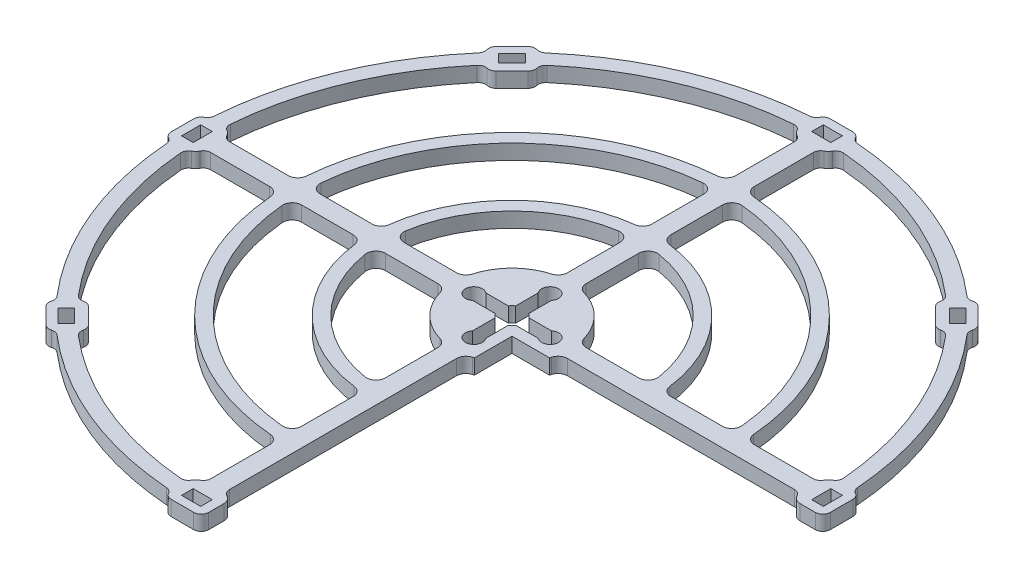
SolidWorks part; units mm, degrees
ref_plane "Front Plane" through (0, 0, 0) normal (0, 0, 1) x (1, 0, 0)
ref_plane "Top Plane" through (0, 0, 0) normal (0, 1, 0) x (1, 0, 0)
ref_plane "Right Plane" through (0, 0, 0) normal (1, 0, 0) x (0, 0, -1)
sketch "Sketch1" plane through (0, 0, 0) normal (0, 1, 0) x (1, 0, 0)
  line L0 (15.5, 0) -> (37.6667, 0) construction
  line L1 (2.5, -56.2778) -> (2.5, -59.7811)
  line L2 (37.6667, 0) -> (59.8333, 0) construction
  line L3 (2.5, -34.0751) -> (2.5, -37.5836)
  line L4 (-2.5, 85.9637) -> (2.5, 85.9637) construction
  line L5 (-2.5, 85.9637) -> (-2.5, -85.9637) construction
  line L6 (-2.5, -85.9637) -> (2.5, -85.9637) construction
  line L7 (2.5, 85.9637) -> (2.5, -85.9637) construction
  line L8 (-2.5, 85.9637) -> (2.5, -85.9637) construction
  line L9 (-2.5, -85.9637) -> (2.5, 85.9637) construction
  line L10 (-85.9637, 2.5) -> (85.9637, 2.5) construction
  line L11 (-85.9637, 2.5) -> (-85.9637, -2.5) construction
  line L12 (-85.9637, -2.5) -> (85.9637, -2.5) construction
  line L13 (85.9637, 2.5) -> (85.9637, -2.5) construction
  line L14 (-85.9637, 2.5) -> (85.9637, -2.5) construction
  line L15 (-85.9637, -2.5) -> (85.9637, 2.5) construction
  line L17 (2.5, -81.9619) -> (2.5, -85.9637)
  line L18 (34.0751, -2.5) -> (37.5836, -2.5)
  line L20 (81.9619, -2.5) -> (85.9637, -2.5)
  line L21 (56.2778, -2.5) -> (59.7811, -2.5)
  line L22 (59.8333, 0) -> (82, 0) construction
  arc A0 (85.9637, -2.5) -> (2.5, -85.9637) centre (0, 0) ccw
  arc A1 (37.5836, -2.5) -> (2.5, -37.5836) centre (0, 0) ccw
  circle A3 centre (0, 0) radius 15.5
  arc A4 (34.0751, -2.5) -> (2.5, -34.0751) centre (0, 0) ccw
  arc A6 (81.9619, -2.5) -> (2.5, -81.9619) centre (0, 0) ccw
  arc A7 (56.2778, -2.5) -> (2.5, -56.2778) centre (0, 0) ccw
  arc A8 (59.7811, -2.5) -> (2.5, -59.7811) centre (0, 0) ccw
  point P10 (0, 0)
  point P26 (77.9162, 0)
  dimension "D1" = 172
  dimension "D2" = 31
  dimension "D3" = 3.5
  dimension "D4" = 3.5
  dimension "D5" = 4
  dimension "D6" = 5
  dimension "D7" = 5
extrude "Boss-Extrude1" add sketch "Sketch1" along normal blind 4
sketch "Sketch2" plane through (0, 4, 0) normal (0, 1, 0) x (1, 0, 0)
  line L0 (-2.5, 85.9637) -> (2.5, 85.9637)
  line L1 (2.5, 85.9637) -> (2.5, -85.9637)
  line L2 (2.5, -85.9637) -> (-2.5, -85.9637)
  line L3 (-2.5, -85.9637) -> (-2.5, 85.9637)
  line L4 (-85.9637, 2.5) -> (-85.9637, -2.5)
  line L5 (-85.9637, -2.5) -> (85.9637, -2.5)
  line L6 (85.9637, -2.5) -> (85.9637, 2.5)
  line L7 (85.9637, 2.5) -> (-85.9637, 2.5)
  arc M1 (2.5, -81.9619) -> (81.9619, -2.5) centre (0, 0) cw
extrude "Boss-Extrude2" add sketch "Sketch2" against normal up to surface (4 mm away) contours L3 L7 L5 M1 | L7 L1 L3 M1 | L7 L1 L5 M1 | L5 L3 L1 M1 up to face at (0, 0, 15.5)
sketch "Sketch3" plane through (0, 4, 0) normal (0, 1, 0) x (1, 0, 0)
  line L0 (2.7386, 1.75) -> (8.7458, 1.75)
  line L1 (-1.75, 2.7386) -> (1.75, 2.7386) construction
  line L2 (-1.75, 2.7386) -> (-1.75, 8.7458)
  line L3 (-1.75, 8.7458) -> (1.75, 8.7458) construction
  line L4 (1.75, 2.7386) -> (1.75, 8.7458)
  line L5 (2.7386, -1.75) -> (8.7458, -1.75)
  line L6 (1.75, -2.7386) -> (1.75, -8.7458)
  line L7 (-1.75, -2.7386) -> (-1.75, -8.7458)
  line L8 (-2.7386, -1.75) -> (-8.7458, -1.75)
  line L9 (-2.7386, 1.75) -> (-8.7458, 1.75)
  line L10 (0, 0) -> (1.75, 2.7386) construction
  arc A0 (-1.75, 2.7386) -> (-2.7386, 1.75) centre (0, 0) ccw
  arc A1 (1.75, 8.7458) -> (-1.75, 8.7458) centre (0, 10.16) ccw
  arc A2 (8.7458, -1.75) -> (8.7458, 1.75) centre (10.16, 0) ccw
  arc A3 (-1.75, -8.7458) -> (1.75, -8.7458) centre (0, -10.16) ccw
  arc A4 (-8.7458, 1.75) -> (-8.7458, -1.75) centre (-10.16, 0) ccw
  arc A5 (-2.7386, -1.75) -> (-1.75, -2.7386) centre (0, 0) ccw
  arc A6 (1.75, -2.7386) -> (2.7386, -1.75) centre (0, 0) ccw
  arc A7 (2.7386, 1.75) -> (1.75, 2.7386) centre (0, 0) ccw
  point P13 (0, 2.7386)
  dimension "D1" = 4.5
  dimension "D2" = 3.25
  dimension "D3" = 10.16
  dimension "D4" = 3.5
  dimension "D5" = 4
extrude "Cut-Extrude1" cut sketch "Sketch3" against normal up to surface (4 mm away) up to face at (0.8198, 0, 0.8198)
sketch "Sketch4" plane through (0, 4, 0) normal (0, 1, 0) x (1, 0, 0)
  line L0 (0, -86) -> (0, -82) construction
  line L5 (-5, 81.8474) -> (-5, 85.8545)
  line L6 (-3, 87.8545) -> (3, 87.8545)
  line L7 (5, 85.8545) -> (5, 81.8474)
  line L8 (2.5, 37.5836) -> (2.5, 56.2778) construction
  line L9 (2.5, 79.3474) -> (-2.5, 79.3474)
  line L10 (-2.5, 81.9619) -> (-2.5, 59.7811) construction
  line L19 (0, 0) -> (115.2239, 115.2239) construction
  line L20 (2.5, 34.0751) -> (2.5, 15.2971) construction
  line L21 (54.3393, 61.4104) -> (57.1728, 64.2439)
  line L22 (59.9962, 64.2439) -> (64.2439, 59.9962)
  line L24 (64.2439, 57.1728) -> (61.4104, 54.3393)
  line L26 (58.587, 54.3393) -> (54.3393, 58.587)
  line L27 (55.7561, 62.8271) -> (62.8271, 55.7561) construction
  line L28 (81.8474, 5) -> (85.8545, 5)
  line L29 (87.8545, 3) -> (87.8545, -3)
  line L30 (85.8545, -5) -> (81.8474, -5)
  line L31 (79.3474, -2.5) -> (79.3474, 2.5)
  line L32 (5, -81.8474) -> (5, -85.8545)
  line L33 (3, -87.8545) -> (-3, -87.8545)
  line L34 (-5, -85.8545) -> (-5, -81.8474)
  line L35 (-2.5, -79.3474) -> (2.5, -79.3474)
  line L36 (-81.8474, -5) -> (-85.8545, -5)
  line L37 (-87.8545, -3) -> (-87.8545, 3)
  line L38 (-85.8545, 5) -> (-81.8474, 5)
  line L39 (-79.3474, 2.5) -> (-79.3474, -2.5)
  line L40 (0, 0) -> (2.5, 79.3474) construction
  line L41 (61.4104, -54.3393) -> (64.2439, -57.1728) [skipped]
  line L42 (64.2439, -59.9962) -> (59.9962, -64.2439) [skipped]
  line L43 (57.1728, -64.2439) -> (54.3393, -61.4104) [skipped]
  line L44 (54.3393, -58.587) -> (58.587, -54.3393) [skipped]
  line L45 (-54.3393, -61.4104) -> (-57.1728, -64.2439)
  line L46 (-59.9962, -64.2439) -> (-64.2439, -59.9962)
  line L47 (-64.2439, -57.1728) -> (-61.4104, -54.3393)
  line L48 (-58.587, -54.3393) -> (-54.3393, -58.587)
  line L49 (-61.4104, 54.3393) -> (-64.2439, 57.1728)
  line L50 (-64.2439, 59.9962) -> (-59.9962, 64.2439)
  line L51 (-57.1728, 64.2439) -> (-54.3393, 61.4104)
  line L52 (-54.3393, 58.587) -> (-58.587, 54.3393)
  line L53 (0, 0) -> (58.587, 54.3393) construction
  circle A0 centre (0, 0) radius 84 construction
  arc A1 (-5, 85.8545) -> (-3, 87.8545) centre (-3, 85.8545) cw
  arc A2 (3, 87.8545) -> (5, 85.8545) centre (3, 85.8545) cw
  arc A3 (5, 81.8474) -> (2.5, 79.3474) centre (2.5, 81.8474) cw
  arc A4 (-2.5, 79.3474) -> (-5, 81.8474) centre (-2.5, 81.8474) cw
  arc A5 (85.9637, -2.5) -> (2.5, -85.9637) centre (0, 0) ccw construction
  arc A6 (57.1728, 64.2439) -> (59.9962, 64.2439) centre (58.5845, 62.8322) cw
  arc A8 (-2.5, 81.9619) -> (-81.9619, 2.5) centre (0, 0) ccw construction
  arc A24 (85.9637, -2.5) -> (2.5, -85.9637) centre (0, 0) ccw construction
  arc A25 (64.2439, 59.9962) -> (64.2439, 57.1728) centre (62.8322, 58.5845) cw
  arc A26 (-81.9619, -2.5) -> (-2.5, -81.9619) centre (0, 0) ccw construction
  arc A27 (61.4104, 54.3393) -> (58.587, 54.3393) centre (59.9987, 55.751) cw
  arc A28 (54.3393, 58.587) -> (54.3393, 61.4104) centre (55.751, 59.9987) cw
  arc A29 (79.3474, 2.5) -> (81.8474, 5) centre (81.8474, 2.5) cw
  arc A31 (81.9619, 2.5) -> (2.5, 81.9619) centre (0, 0) ccw construction
  arc A32 (85.8545, 5) -> (87.8545, 3) centre (85.8545, 3) cw
  arc A33 (87.8545, -3) -> (85.8545, -5) centre (85.8545, -3) cw
  arc A34 (81.8474, -5) -> (79.3474, -2.5) centre (81.8474, -2.5) cw
  arc A35 (2.5, -79.3474) -> (5, -81.8474) centre (2.5, -81.8474) cw
  arc A36 (5, -85.8545) -> (3, -87.8545) centre (3, -85.8545) cw
  arc A37 (-3, -87.8545) -> (-5, -85.8545) centre (-3, -85.8545) cw
  arc A38 (-5, -81.8474) -> (-2.5, -79.3474) centre (-2.5, -81.8474) cw
  arc A39 (-79.3474, -2.5) -> (-81.8474, -5) centre (-81.8474, -2.5) cw
  arc A40 (-85.8545, -5) -> (-87.8545, -3) centre (-85.8545, -3) cw
  arc A41 (-87.8545, 3) -> (-85.8545, 5) centre (-85.8545, 3) cw
  arc A42 (-81.8474, 5) -> (-79.3474, 2.5) centre (-81.8474, 2.5) cw
  arc A43 (58.587, -54.3393) -> (61.4104, -54.3393) centre (59.9987, -55.751) cw [skipped]
  arc A44 (64.2439, -57.1728) -> (64.2439, -59.9962) centre (62.8322, -58.5845) cw [skipped]
  arc A45 (59.9962, -64.2439) -> (57.1728, -64.2439) centre (58.5845, -62.8322) cw [skipped]
  arc A46 (54.3393, -61.4104) -> (54.3393, -58.587) centre (55.751, -59.9987) cw [skipped]
  arc A47 (-54.3393, -58.587) -> (-54.3393, -61.4104) centre (-55.751, -59.9987) cw
  arc A48 (-57.1728, -64.2439) -> (-59.9962, -64.2439) centre (-58.5845, -62.8322) cw
  arc A49 (-64.2439, -59.9962) -> (-64.2439, -57.1728) centre (-62.8322, -58.5845) cw
  arc A50 (-61.4104, -54.3393) -> (-58.587, -54.3393) centre (-59.9987, -55.751) cw
  arc A51 (-58.587, 54.3393) -> (-61.4104, 54.3393) centre (-59.9987, 55.751) cw
  arc A52 (-64.2439, 57.1728) -> (-64.2439, 59.9962) centre (-62.8322, 58.5845) cw
  arc A53 (-59.9962, 64.2439) -> (-57.1728, 64.2439) centre (-58.5845, 62.8322) cw
  arc A54 (-54.3393, 61.4104) -> (-54.3393, 58.587) centre (-55.751, 59.9987) cw
  point P17 (0, -84)
  point P50 (62.12, 62.12)
  dimension "D1" = 8
  dimension "D2" = 45
  dimension "D3" = 10
  dimension "D4" = 6
  dimension "D6" = 4
  dimension "D8" = 4
  dimension "D5" = 10
extrude "Boss-Extrude5" add sketch "Sketch4" against normal up to surface (4 mm away) up to face at (0, 0, 0)
sketch "Sketch5" plane through (0, 4, 0) normal (0, 1, 0) x (1, 0, 0)
  line L0 (0, -86) -> (0, -82) construction
  line L1 (-2.55, -82.45) -> (2.55, -82.45)
  line L2 (-2.55, -82.45) -> (-2.55, -85.55)
  line L3 (-2.55, -85.55) -> (2.55, -85.55)
  line L4 (2.55, -82.45) -> (2.55, -85.55)
  line L5 (-2.55, -82.45) -> (2.55, -85.55) construction
  line L6 (-2.55, -85.55) -> (2.55, -82.45) construction
  line L7 (-60.1041, -56.4978) -> (-62.2961, -58.6899)
  line L8 (-60.1041, -56.4978) -> (-56.4978, -60.1041)
  line L9 (-56.4978, -60.1041) -> (-58.6899, -62.2961)
  line L10 (-62.2961, -58.6899) -> (-58.6899, -62.2961)
  line L11 (-82.45, 2.55) -> (-85.55, 2.55)
  line L12 (-82.45, 2.55) -> (-82.45, -2.55)
  line L13 (-82.45, -2.55) -> (-85.55, -2.55)
  line L14 (-85.55, 2.55) -> (-85.55, -2.55)
  line L15 (-56.4978, 60.1041) -> (-58.6899, 62.2961)
  line L16 (-56.4978, 60.1041) -> (-60.1041, 56.4978)
  line L17 (-60.1041, 56.4978) -> (-62.2961, 58.6899)
  line L18 (-58.6899, 62.2961) -> (-62.2961, 58.6899)
  line L19 (2.55, 82.45) -> (2.55, 85.55)
  line L20 (2.55, 82.45) -> (-2.55, 82.45)
  line L21 (-2.55, 82.45) -> (-2.55, 85.55)
  line L22 (2.55, 85.55) -> (-2.55, 85.55)
  line L23 (60.1041, 56.4978) -> (62.2961, 58.6899)
  line L24 (60.1041, 56.4978) -> (56.4978, 60.1041)
  line L25 (56.4978, 60.1041) -> (58.6899, 62.2961)
  line L26 (62.2961, 58.6899) -> (58.6899, 62.2961)
  line L27 (82.45, -2.55) -> (85.55, -2.55)
  line L28 (82.45, -2.55) -> (82.45, 2.55)
  line L29 (82.45, 2.55) -> (85.55, 2.55)
  line L30 (85.55, -2.55) -> (85.55, 2.55)
  line L31 (56.4978, -60.1041) -> (58.6899, -62.2961) [skipped]
  line L32 (56.4978, -60.1041) -> (60.1041, -56.4978) [skipped]
  line L33 (60.1041, -56.4978) -> (62.2961, -58.6899) [skipped]
  line L34 (58.6899, -62.2961) -> (62.2961, -58.6899) [skipped]
  line L35 (0, 0) -> (-2.55, -82.45) construction
  circle A0 centre (0, 0) radius 84 construction
  point P0 (0, -84)
  dimension "D1" = 5.1
  dimension "D2" = 3.1
  dimension "D3" = 8
extrude "Cut-Extrude3" cut sketch "Sketch5" against normal through all
sketch "Sketch6" plane through (0, 4, 0) normal (0, 1, 0) x (1, 0, 0)
  line L0 (0, 0) -> (14.7542, -14.7542) construction
  line L1 (4.75, -4.75) -> (14.7542, -4.75)
  line L2 (4.75, -4.75) -> (4.75, -14.7542)
  line L3 (4.75, -14.7542) -> (14.7542, -14.7542)
  line L4 (14.7542, -4.75) -> (14.7542, -14.7542)
  line L5 (2.7386, -1.75) -> (8.7458, -1.75) construction
  arc A0 (2.5, -15.2971) -> (15.2971, -2.5) centre (0, 0) ccw construction
  dimension "D1" = 3
extrude "Cut-Extrude4" cut sketch "Sketch6" against normal through all
fillet "Fillet1" radius 2.5 32 edges at (-2.5, 2, 34.0751) (-2.5, 2, -34.0751) (-15.2971, 2, -2.5) (15.2971, 2, -2.5) (-34.0751, 2, 2.5) (-37.5836, 2, 2.5) (-2.5, 2, 37.5836) (-2.5, 2, -37.5836) (-2.5, 2, 15.2971) (-2.5, 2, -15.2971) (-37.5836, 2, -2.5) (37.5836, 2, -2.5) (-34.0751, 2, -2.5) (34.0751, 2, -2.5) (2.5, 2, -37.5836) (2.5, 2, -15.2971) (2.5, 2, -34.0751) (2.5, 2, 15.2971) (15.2971, 2, 2.5) (-15.2971, 2, 2.5) (-2.5, 2, 56.2778) (-2.5, 2, -56.2778) (2.5, 2, -56.2778) (2.5, 2, -59.7811) (-59.7811, 2, -2.5) (59.7811, 2, -2.5) (-2.5, 2, 59.7811) (-2.5, 2, -59.7811) (-56.2778, 2, -2.5) (56.2778, 2, -2.5) (-59.7811, 2, 2.5) (-56.2778, 2, 2.5)
fillet "Fillet2" radius 2 32 edges at (57.1728, 2, -64.2439) (54.3393, 2, -61.4104) (61.4104, 2, -54.3393) (79.3474, 2, 2.5) (64.2439, 2, -57.1728) (85.8545, 2, -5) (79.3474, 2, -2.5) (81.8474, 2, -5) (-2.5, 2, -79.3474) (-5, 2, -81.8474) (2.5, 2, -79.3474) (5, 2, -81.8474) (-61.4104, 2, -54.3393) (-54.3393, 2, -61.4104) (-79.3474, 2, 2.5) (-81.8474, 2, 5) (-81.8474, 2, -5) (-64.2439, 2, 57.1728) (-57.1728, 2, 64.2439) (-5, 2, 85.8545) (-64.2439, 2, -57.1728) (-85.8545, 2, 5) (2.5, 2, 79.3474) (-54.3393, 2, 61.4104) (-79.3474, 2, -2.5) (5, 2, -85.8545) (-5, 2, -85.8545) (-2.5, 2, 79.3474) (-5, 2, 81.8474) (-61.4104, 2, 54.3393) (-85.8545, 2, -5) (-57.1728, 2, -64.2439)
